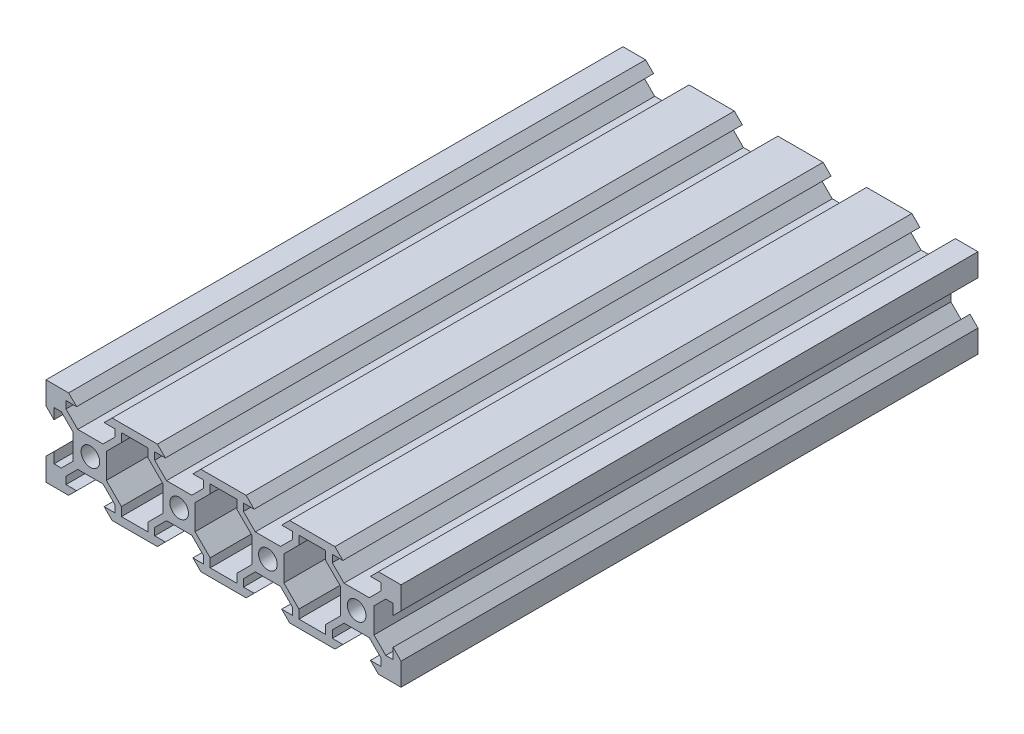
SolidWorks part; units mm, degrees
ref_plane "Plan de face" through (0, 0, 0) normal (0, 0, 1) x (1, 0, 0)
ref_plane "Plan de dessus" through (0, 0, 0) normal (0, 1, 0) x (1, 0, 0)
ref_plane "Plan de droite" through (0, 0, 0) normal (1, 0, 0) x (0, 0, -1)
sketch "Esquisse1" plane through (0, 0, 0) normal (0, 0, 1) x (1, 0, 0)
  line L45 (-65.6277, 8.2661) -> (14.3723, 8.2661)
  line L46 (-65.6277, 8.2661) -> (-65.6277, -11.7339)
  line L47 (-65.6277, -11.7339) -> (14.3723, -11.7339)
  line L48 (14.3723, 8.2661) -> (14.3723, -11.7339)
  dimension "D1" = 80
  dimension "D2" = 20
extrude "Boss.-Extru.1" add sketch "Esquisse1" along normal blind 130
sketch "Esquisse2" plane through (0, 0, 0) normal (0, 0, -1) x (-1, 0, 0)
  line L0 (-14.3723, -11.7339) -> (-14.3723, 8.2661) construction
  line L2 (50.7277, 8.2661) -> (60.5277, 8.2661)
  line L3 (-14.3723, 8.2661) -> (65.6277, 8.2661) construction
  line L4 (60.5277, 8.2661) -> (58.7277, 6.4661)
  line L5 (58.7277, 6.4661) -> (61.1277, 6.4661)
  line L6 (61.1277, 6.4661) -> (61.1277, 4.8261)
  line L7 (61.1277, 4.8261) -> (58.4677, 2.1661)
  line L8 (58.4677, 2.1661) -> (52.7877, 2.1661)
  line L9 (52.7877, 2.1661) -> (50.1277, 4.8261)
  line L10 (50.1277, 4.8261) -> (50.1277, 6.4661)
  line L11 (50.1277, 6.4661) -> (52.5277, 6.4661)
  line L12 (52.5277, 6.4661) -> (50.7277, 8.2661)
  line L43 (65.6277, 8.2661) -> (65.6277, -11.7339) construction
  line L44 (65.6277, 3.1661) -> (65.6277, -6.6339)
  line L45 (65.6277, -6.6339) -> (63.8277, -4.8339)
  line L46 (63.8277, -4.8339) -> (63.8277, -7.2339)
  line L47 (63.8277, -7.2339) -> (62.1877, -7.2339)
  line L48 (62.1877, -7.2339) -> (59.5277, -4.5739)
  line L49 (59.5277, -4.5739) -> (59.5277, 1.1061)
  line L50 (59.5277, 1.1061) -> (62.1877, 3.7661)
  line L51 (62.1877, 3.7661) -> (63.8277, 3.7661)
  line L52 (63.8277, 3.7661) -> (63.8277, 1.3661)
  line L53 (63.8277, 1.3661) -> (65.6277, 3.1661)
  line L54 (60.5277, -11.7339) -> (50.7277, -11.7339)
  line L55 (50.7277, -11.7339) -> (52.5277, -9.9339)
  line L56 (52.5277, -9.9339) -> (50.1277, -9.9339)
  line L57 (50.1277, -9.9339) -> (50.1277, -8.2939)
  line L58 (50.1277, -8.2939) -> (52.7877, -5.6339)
  line L59 (52.7877, -5.6339) -> (58.4677, -5.6339)
  line L60 (58.4677, -5.6339) -> (61.1277, -8.2939)
  line L61 (61.1277, -8.2939) -> (61.1277, -9.9339)
  line L62 (61.1277, -9.9339) -> (58.7277, -9.9339)
  line L63 (58.7277, -9.9339) -> (60.5277, -11.7339)
  line L64 (55.6277, -1.7339) -> (58.4677, 2.1661) construction
  line L65 (55.6277, -1.7339) -> (59.5277, -4.5739) construction
  line L66 (30.7277, 8.2661) -> (40.5277, 8.2661)
  line L67 (40.5277, 8.2661) -> (38.7277, 6.4661)
  line L68 (38.7277, 6.4661) -> (41.1277, 6.4661)
  line L69 (41.1277, 6.4661) -> (41.1277, 4.8261)
  line L70 (41.1277, 4.8261) -> (38.4677, 2.1661)
  line L71 (38.4677, 2.1661) -> (32.7877, 2.1661)
  line L72 (32.7877, 2.1661) -> (30.1277, 4.8261)
  line L73 (30.1277, 4.8261) -> (30.1277, 6.4661)
  line L74 (30.1277, 6.4661) -> (32.5277, 6.4661)
  line L75 (32.5277, 6.4661) -> (30.7277, 8.2661)
  line L76 (40.5277, -11.7339) -> (30.7277, -11.7339)
  line L77 (30.7277, -11.7339) -> (32.5277, -9.9339)
  line L78 (32.5277, -9.9339) -> (30.1277, -9.9339)
  line L79 (30.1277, -9.9339) -> (30.1277, -8.2939)
  line L80 (30.1277, -8.2939) -> (32.7877, -5.6339)
  line L81 (32.7877, -5.6339) -> (38.4677, -5.6339)
  line L82 (38.4677, -5.6339) -> (41.1277, -8.2939)
  line L83 (41.1277, -8.2939) -> (41.1277, -9.9339)
  line L84 (41.1277, -9.9339) -> (38.7277, -9.9339)
  line L85 (38.7277, -9.9339) -> (40.5277, -11.7339)
  line L86 (35.6277, -1.7339) -> (38.4677, 2.1661) construction
  line L87 (10.7277, 8.2661) -> (20.5277, 8.2661)
  line L88 (20.5277, 8.2661) -> (18.7277, 6.4661)
  line L89 (18.7277, 6.4661) -> (21.1277, 6.4661)
  line L90 (21.1277, 6.4661) -> (21.1277, 4.8261)
  line L91 (21.1277, 4.8261) -> (18.4677, 2.1661)
  line L92 (18.4677, 2.1661) -> (12.7877, 2.1661)
  line L93 (12.7877, 2.1661) -> (10.1277, 4.8261)
  line L94 (10.1277, 4.8261) -> (10.1277, 6.4661)
  line L95 (10.1277, 6.4661) -> (12.5277, 6.4661)
  line L96 (12.5277, 6.4661) -> (10.7277, 8.2661)
  line L97 (20.5277, -11.7339) -> (10.7277, -11.7339)
  line L98 (10.7277, -11.7339) -> (12.5277, -9.9339)
  line L99 (12.5277, -9.9339) -> (10.1277, -9.9339)
  line L100 (10.1277, -9.9339) -> (10.1277, -8.2939)
  line L101 (10.1277, -8.2939) -> (12.7877, -5.6339)
  line L102 (12.7877, -5.6339) -> (18.4677, -5.6339)
  line L103 (18.4677, -5.6339) -> (21.1277, -8.2939)
  line L104 (21.1277, -8.2939) -> (21.1277, -9.9339)
  line L105 (21.1277, -9.9339) -> (18.7277, -9.9339)
  line L106 (18.7277, -9.9339) -> (20.5277, -11.7339)
  line L107 (15.6277, -1.7339) -> (18.4677, 2.1661) construction
  line L108 (-9.2723, 8.2661) -> (0.5277, 8.2661)
  line L109 (0.5277, 8.2661) -> (-1.2723, 6.4661)
  line L110 (-1.2723, 6.4661) -> (1.1277, 6.4661)
  line L111 (1.1277, 6.4661) -> (1.1277, 4.8261)
  line L112 (1.1277, 4.8261) -> (-1.5323, 2.1661)
  line L113 (-1.5323, 2.1661) -> (-7.2123, 2.1661)
  line L114 (-7.2123, 2.1661) -> (-9.8723, 4.8261)
  line L115 (-9.8723, 4.8261) -> (-9.8723, 6.4661)
  line L116 (-9.8723, 6.4661) -> (-7.4723, 6.4661)
  line L117 (-7.4723, 6.4661) -> (-9.2723, 8.2661)
  line L118 (0.5277, -11.7339) -> (-9.2723, -11.7339)
  line L119 (-9.2723, -11.7339) -> (-7.4723, -9.9339)
  line L120 (-7.4723, -9.9339) -> (-9.8723, -9.9339)
  line L121 (-9.8723, -9.9339) -> (-9.8723, -8.2939)
  line L122 (-9.8723, -8.2939) -> (-7.2123, -5.6339)
  line L123 (-7.2123, -5.6339) -> (-1.5323, -5.6339)
  line L124 (-1.5323, -5.6339) -> (1.1277, -8.2939)
  line L125 (1.1277, -8.2939) -> (1.1277, -9.9339)
  line L126 (1.1277, -9.9339) -> (-1.2723, -9.9339)
  line L127 (-1.2723, -9.9339) -> (0.5277, -11.7339)
  line L128 (-4.3723, -1.7339) -> (-1.5323, 2.1661) construction
  line L129 (-14.3723, -6.6339) -> (-14.3723, 3.1661)
  line L130 (-14.3723, 3.1661) -> (-12.5723, 1.3661)
  line L131 (-12.5723, 1.3661) -> (-12.5723, 3.7661)
  line L132 (-12.5723, 3.7661) -> (-10.9323, 3.7661)
  line L133 (-10.9323, 3.7661) -> (-8.2723, 1.1061)
  line L134 (-8.2723, 1.1061) -> (-8.2723, -4.5739)
  line L135 (-8.2723, -4.5739) -> (-10.9323, -7.2339)
  line L136 (-10.9323, -7.2339) -> (-12.5723, -7.2339)
  line L137 (-12.5723, -7.2339) -> (-12.5723, -4.8339)
  line L138 (-12.5723, -4.8339) -> (-14.3723, -6.6339)
  line L139 (-4.3723, -1.7339) -> (-1.5323, 2.1661) construction
  line L140 (-4.3723, -1.7339) -> (-8.2723, 1.1061) construction
  circle A0 centre (55.6277, -1.7339) radius 2.1
  circle A1 centre (35.6277, -1.7339) radius 2.1
  circle A2 centre (15.6277, -1.7339) radius 2.1
  circle A3 centre (-4.3723, -1.7339) radius 2.1
  point P5 (-14.3723, -1.7339)
  point P17 (55.6277, 2.1661)
  point P54 (10.6277, 13.2661)
  dimension "D1" = 4.2
  dimension "D2" = 135
  dimension "D3" = 1.64
  dimension "D4" = 5.68
  dimension "D5" = 1.8
  dimension "D6" = 6.2
  dimension "D7" = 11
  dimension "D8" = 10
  dimension "D10" = 90
  dimension "D13" = 90
  dimension "D11" = 4
  dimension "D9" = 3
  dimension "D12" = 2
extrude "Enlèv. mat.-Extru.1" cut sketch "Esquisse2" against normal up to next
sketch "Esquisse3" plane through (0, 0, 0) normal (0, 0, -1) x (-1, 0, 0)
  line L0 (2.6183, 6.4661) -> (8.6372, 6.4661)
  line L1 (8.6372, 6.4661) -> (8.6372, 4.5061)
  line L2 (8.6372, 4.5061) -> (12.0372, 1.1061)
  line L3 (12.0372, 1.1061) -> (12.0372, -4.5739)
  line L4 (12.0372, -4.5739) -> (8.6372, -7.9739)
  line L5 (8.6372, -7.9739) -> (8.6372, -9.9339)
  line L6 (8.6372, -9.9339) -> (2.6183, -9.9339)
  line L7 (2.6183, -9.9339) -> (2.6183, -7.9739)
  line L8 (2.6183, -7.9739) -> (-0.7817, -4.5739)
  line L9 (-0.7817, -4.5739) -> (-0.7817, 1.1061)
  line L10 (-0.7817, 1.1061) -> (2.6183, 4.5061)
  line L11 (2.6183, 4.5061) -> (2.6183, 6.4661)
  line L12 (0.5277, 8.2661) -> (10.7277, 8.2661) construction
  line L13 (-1.2723, -9.9339) -> (1.1277, -9.9339) construction
  line L14 (1.1277, 6.4661) -> (-1.2723, 6.4661) construction
  line L15 (22.6183, 6.4661) -> (28.6372, 6.4661)
  line L16 (28.6372, 6.4661) -> (28.6372, 4.5061)
  line L17 (28.6372, 4.5061) -> (32.0372, 1.1061)
  line L18 (32.0372, 1.1061) -> (32.0372, -4.5739)
  line L19 (32.0372, -4.5739) -> (28.6372, -7.9739)
  line L20 (28.6372, -7.9739) -> (28.6372, -9.9339)
  line L21 (28.6372, -9.9339) -> (22.6183, -9.9339)
  line L22 (22.6183, -9.9339) -> (22.6183, -7.9739)
  line L23 (22.6183, -7.9739) -> (19.2183, -4.5739)
  line L24 (19.2183, -4.5739) -> (19.2183, 1.1061)
  line L25 (19.2183, 1.1061) -> (22.6183, 4.5061)
  line L26 (22.6183, 4.5061) -> (22.6183, 6.4661)
  line L27 (42.6183, 6.4661) -> (48.6372, 6.4661)
  line L28 (48.6372, 6.4661) -> (48.6372, 4.5061)
  line L29 (48.6372, 4.5061) -> (52.0372, 1.1061)
  line L30 (52.0372, 1.1061) -> (52.0372, -4.5739)
  line L31 (52.0372, -4.5739) -> (48.6372, -7.9739)
  line L32 (48.6372, -7.9739) -> (48.6372, -9.9339)
  line L33 (48.6372, -9.9339) -> (42.6183, -9.9339)
  line L34 (42.6183, -9.9339) -> (42.6183, -7.9739)
  line L35 (42.6183, -7.9739) -> (39.2183, -4.5739)
  line L36 (39.2183, -4.5739) -> (39.2183, 1.1061)
  line L37 (39.2183, 1.1061) -> (42.6183, 4.5061)
  line L38 (42.6183, 4.5061) -> (42.6183, 6.4661)
  circle A0 centre (-4.3723, -1.7339) radius 2.1 construction
  circle A1 centre (-4.3723, -1.7339) radius 2.1 construction
  point P13 (5.6277, 6.4661)
  point P16 (5.6277, 8.2661)
  point P28 (-0.7817, -1.7339)
  point P29 (12.0372, -1.7339)
  dimension "D1" = 5.68
  dimension "D2" = 1.96
  dimension "D3" = 3
extrude "Enlèv. mat.-Extru.2" cut sketch "Esquisse3" against normal up to next
